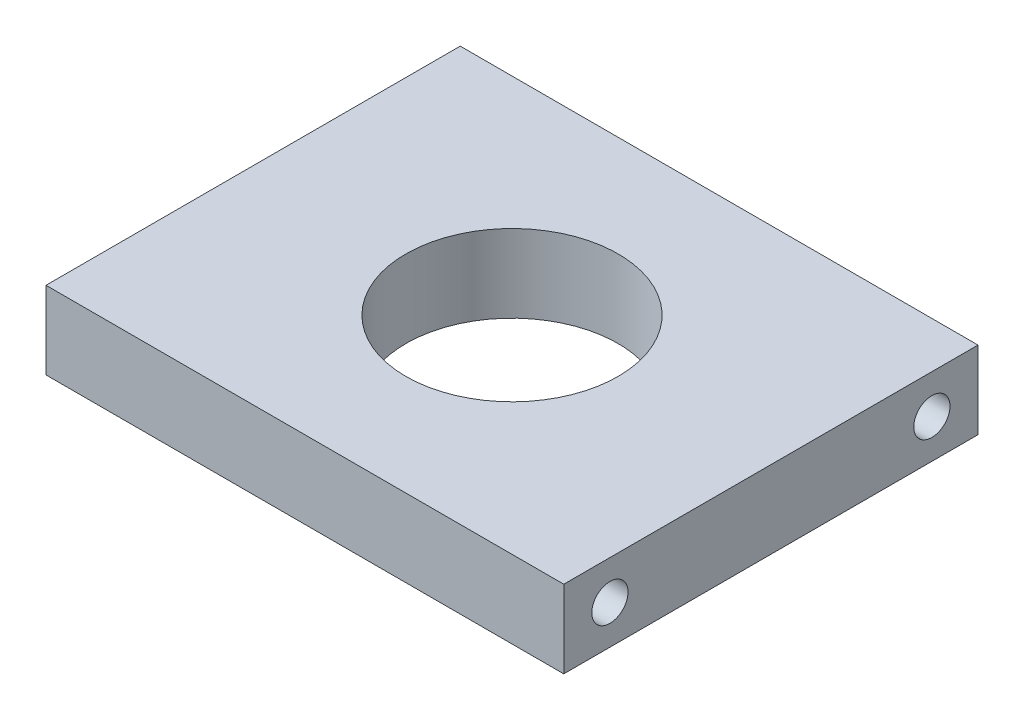
SolidWorks part; units mm, degrees
ref_plane "Front Plane" through (0, 0, 0) normal (0, 0, 1) x (1, 0, 0)
ref_plane "Top Plane" through (0, 0, 0) normal (0, 1, 0) x (1, 0, 0)
ref_plane "Right Plane" through (0, 0, 0) normal (1, 0, 0) x (0, 0, -1)
sketch "Sketch1" plane through (0, 0, 0) normal (0, 1, 0) x (1, 0, 0)
  line L1 (-50, -40) -> (50, -40)
  line L2 (-50, -40) -> (-50, 40)
  line L3 (-50, 40) -> (50, 40)
  line L4 (50, -40) -> (50, 40)
  line L5 (-50, -40) -> (50, 40) construction
  line L6 (-50, 40) -> (50, -40) construction
  circle A0 centre (0, 0) radius 20.5
  point P0 (0, 0)
  dimension "D1" = 100
  dimension "D2" = 80
extrude "Boss-Extrude1" add sketch "Sketch1" along normal blind 15
sketch "Sketch2" plane through (50, 0, 0) normal (1, 0, 0) x (0, 0, -1)
  circle A0 centre (-31.0915, 7.5) radius 3.5
  circle A1 centre (31.0915, 7.5) radius 3.5
extrude "Cut-Extrude1" cut sketch "Sketch2" against normal blind 100
